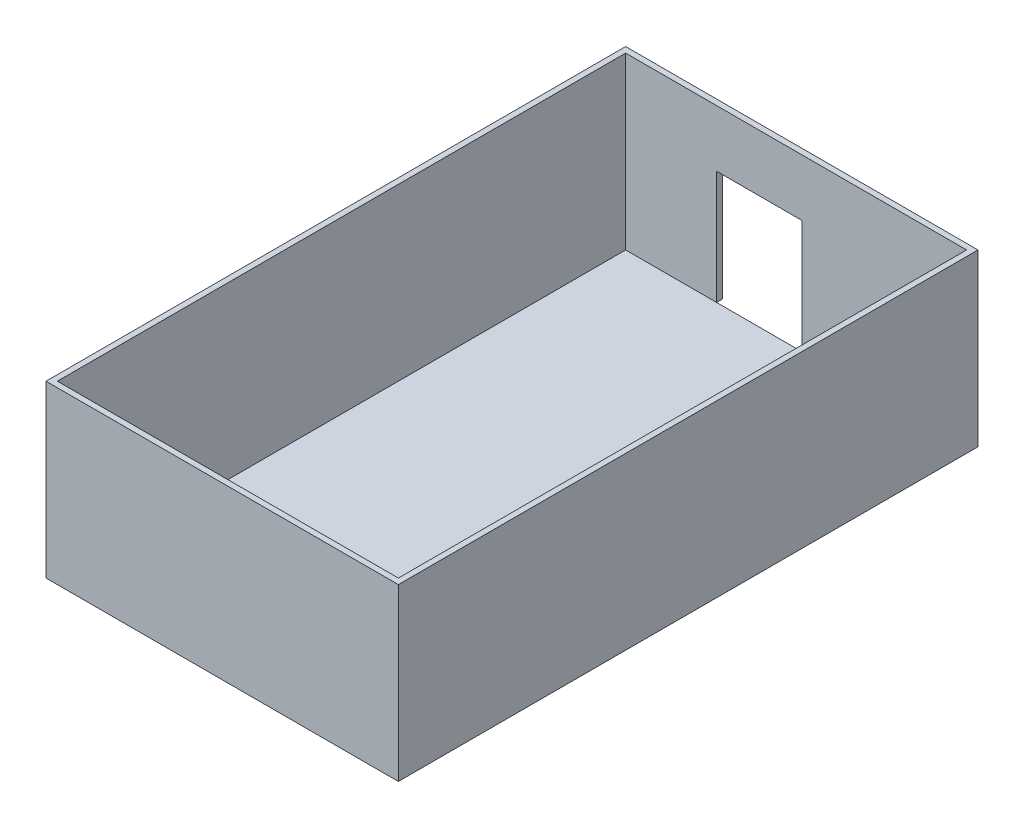
SolidWorks part; units mm, degrees
ref_plane "Front" through (0, 0, 0) normal (0, 0, 1) x (1, 0, 0)
ref_plane "Top" through (0, 0, 0) normal (0, 1, 0) x (1, 0, 0)
ref_plane "Right" through (0, 0, 0) normal (1, 0, 0) x (0, 0, -1)
sketch "Sketch1" plane through (0, 0, 0) normal (0, 1, 0) x (1, 0, 0)
  line L1 (0, 0) -> (-6000, 0)
  line L2 (0, 0) -> (0, 10000)
  line L3 (0, 10000) -> (-6000, 10000)
  line L4 (-6000, 0) -> (-6000, 10000)
  dimension "D1" = 6000
  dimension "D2" = 10000
extrude "Boss-Extrude1" add sketch "Sketch1" along normal blind 10
sketch "Sketch3" plane through (0, 10, 0) normal (0, 1, 0) x (1, 0, 0)
  line L0 (100, -100) -> (100, 10100)
  line L1 (100, 10100) -> (-6100, 10100)
  line L2 (-6100, 10100) -> (-6100, -100)
  line L3 (-6100, -100) -> (100, -100)
  line L4 (0, 0) -> (0, 10000)
  line L5 (0, 10000) -> (-6000, 10000)
  line L6 (-6000, 10000) -> (-6000, 0)
  line L7 (-6000, 0) -> (0, 0)
  line L8 (0, 0) -> (0, 10000)
  line L9 (0, 10000) -> (-6000, 10000)
  line L10 (-6000, 10000) -> (-6000, 0)
  line L11 (-6000, 0) -> (0, 0)
  dimension "D1" = 0
  dimension "D2" = 100
extrude "Boss-Extrude2" add sketch "Sketch3" along normal blind 3000 separate body
sketch "Sketch4" plane through (0, 0, -10100) normal (0, 0, -1) x (-1, 0, 0)
  line L0 (-100, 10) -> (6100, 10) construction
  line L1 (4400, 10) -> (2900, 10)
  line L2 (4400, 10) -> (4400, 2010)
  line L3 (4400, 2010) -> (2900, 2010)
  line L4 (2900, 10) -> (2900, 2010)
  line L5 (-100, 3010) -> (-100, 10) construction
  dimension "D1" = 3000
  dimension "D2" = 2000
  dimension "D3" = 1500
extrude "Cut-Extrude1" cut sketch "Sketch4" against normal blind 100
